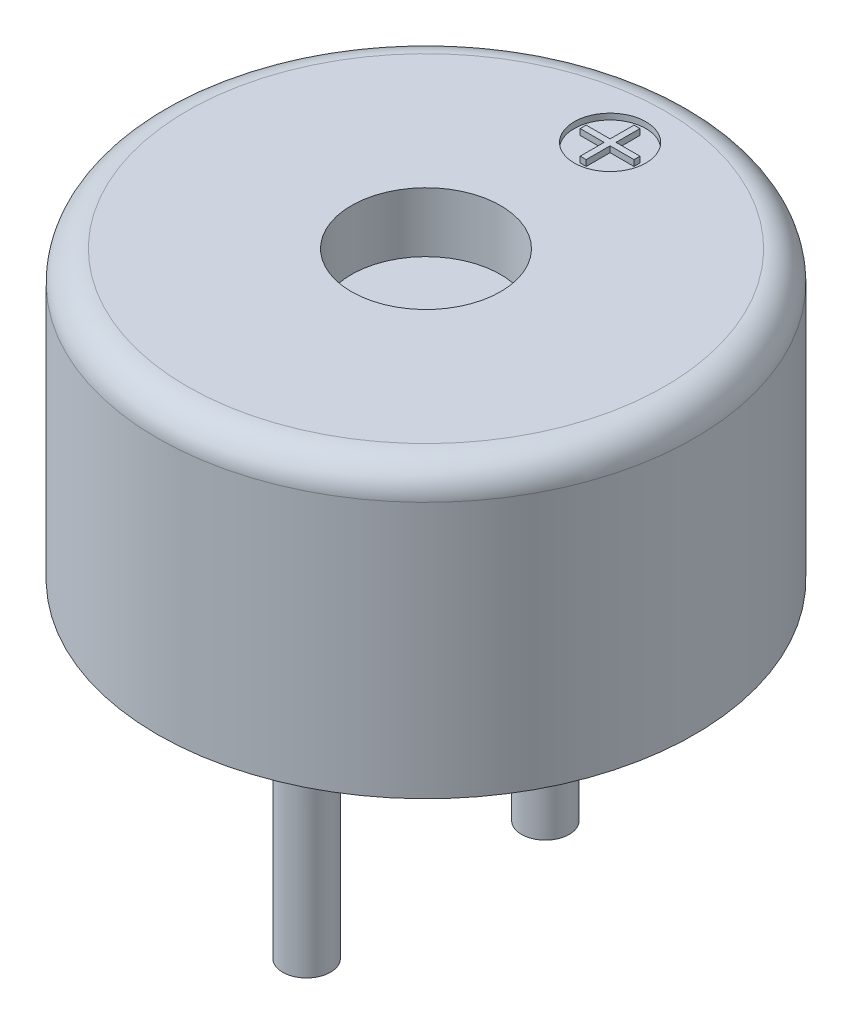
SolidWorks part; units mm, degrees
ref_plane "Front" through (0, 0, 0) normal (0, 0, 1) x (1, 0, 0)
ref_plane "Top" through (0, 0, 0) normal (0, 1, 0) x (1, 0, 0)
ref_plane "Right" through (0, 0, 0) normal (1, 0, 0) x (0, 0, -1)
sketch "Sketch1" plane through (0, 0, 0) normal (0, 1, 0) x (1, 0, 0)
  circle A0 centre (0, 0) radius 4.5
  dimension "D1" = 9
extrude "Extrude1" add sketch "Sketch1" along normal blind 4.8
fillet "Fillet1" radius 0.5 1 edges at (0, 4.8, 4.5)
sketch "Sketch2" plane through (0, 4.8, 0) normal (0, 1, 0) x (1, 0, 0)
  circle A0 centre (0, 0) radius 1.25
  dimension "D2" = 2.5
sketch "Sketch6" plane through (0, 0, 0) normal (0, -1, 0) x (1, 0, 0)
  circle A0 centre (0, -2) radius 0.4
  circle A1 centre (0, 2) radius 0.4
  dimension "D1" = 0.8
  dimension "D2" = 0.8
  dimension "D3" = 2
  dimension "D4" = 2
extrude "Extrude6" add sketch "Sketch6" along normal blind 4.5
extrude "Cut-Extrude2" cut sketch "Sketch2" against normal blind 1
sketch "Sketch8" plane through (0, 4.8, 0) normal (0, 1, 0) x (1, 0, 0)
  line L0 (0, 3.7685) -> (0, 2.3896) construction
  line L1 (0.7718, 3.0838) -> (-0.6047, 3.0838) construction
  line L2 (0.05, 3.5338) -> (-0.05, 3.5338)
  line L3 (-0.05, 3.5338) -> (-0.05, 3.1338)
  line L4 (-0.05, 3.1338) -> (-0.45, 3.1338)
  line L5 (-0.45, 3.1338) -> (-0.45, 3.0338)
  line L6 (0.45, 3.1338) -> (0.45, 3.0338)
  line L7 (0.05, 3.1338) -> (0.45, 3.1338)
  line L8 (0.05, 3.5338) -> (0.05, 3.1338)
  line L9 (0.05, 3.0338) -> (0.45, 3.0338)
  line L10 (0.05, 2.6338) -> (0.05, 3.0338)
  line L11 (0.05, 2.6338) -> (-0.05, 2.6338)
  line L12 (-0.05, 2.6338) -> (-0.05, 3.0338)
  line L13 (-0.05, 3.0338) -> (-0.45, 3.0338)
  circle A0 centre (0, 3.0838) radius 0.6
  point P15 (0, 3.5338)
  point P16 (0.45, 3.0838)
  point P22 (-0.45, 3.0838)
  dimension "D1" = 1.2
  dimension "D2" = 0.4
  dimension "D3" = 0.05
extrude "Cut-Extrude3" cut sketch "Sketch8" against normal blind 0.1 contours A0
